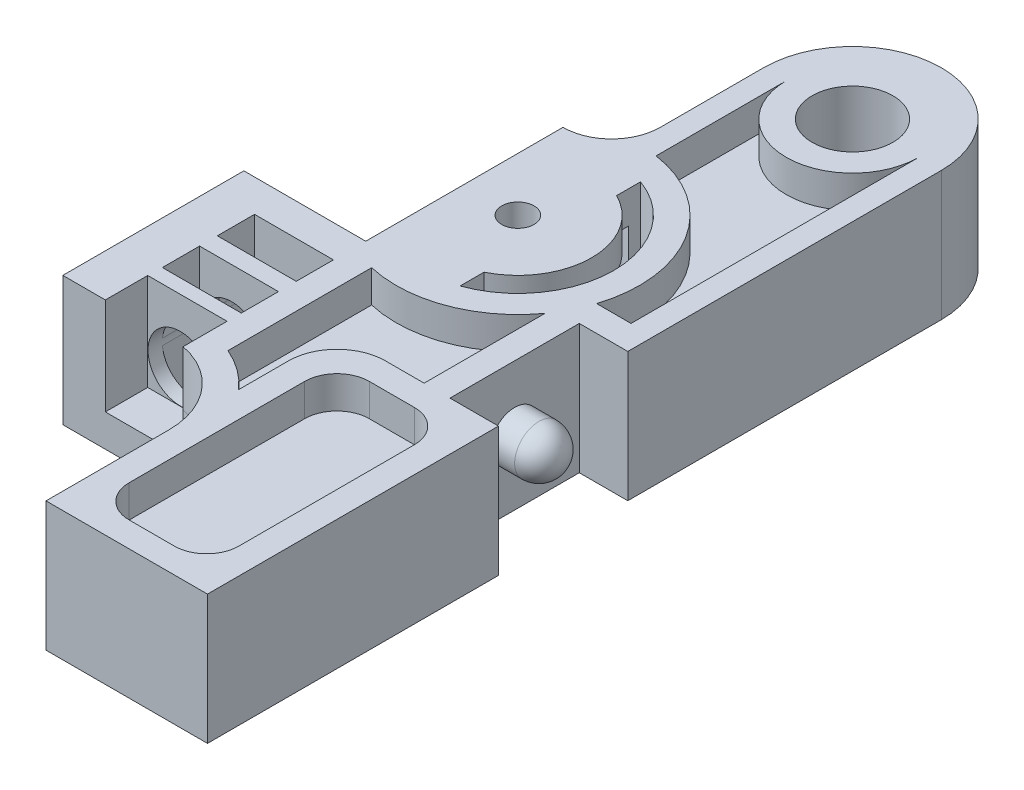
SolidWorks part; units mm, degrees
ref_plane "Front Plane" through (0, 0, 0) normal (0, 0, 1) x (1, 0, 0)
ref_plane "Top Plane" through (0, 0, 0) normal (0, 1, 0) x (1, 0, 0)
ref_plane "Right Plane" through (0, 0, 0) normal (1, 0, 0) x (0, 0, -1)
sketch "Sketch1" plane through (0, 0, 0) normal (0, 1, 0) x (1, 0, 0)
  line L1 (-21.56, 0) -> (-0.01, 0)
  line L2 (-21.56, 0) -> (-21.56, 50.9)
  line L3 (-21.56, 50.9) -> (-0.01, 50.9)
  line L4 (-0.01, 0) -> (-0.01, 50.9)
  dimension "D1" = 21.55
  dimension "D2" = 50.9
extrude "Boss-Extrude1" add sketch "Sketch1" along normal blind 8
sketch "Sketch2" plane through (0, 8, 0) normal (0, 1, 0) x (1, 0, 0)
  line L0 (-0.01, 0) -> (-0.01, 50.9) construction
  line L1 (-0.01, 50.9) -> (-21.56, 50.9) construction
  line L2 (-11.01, 45.4) -> (-11.01, 0) construction
  line L3 (-11.01, 39.0106) -> (-11.01, 45.4)
  line L4 (0, 0) -> (-0.01, 18)
  line L5 (-21.56, 0) -> (-0.01, 0) construction
  line L6 (4.9089, 18.5) -> (-33.8122, 18.5) construction
  line L7 (-37.2568, 26.1) -> (28.1891, 26.1) construction
  line L8 (-37.2568, 36) -> (-12.642, 36) construction
  line L9 (-14.0206, 36) -> (-14.0206, 23.8)
  line L10 (-14.0206, 23.8) -> (-21.56, 23.8)
  line L11 (-21.56, 50.9) -> (-21.56, 0) construction
  line L12 (-21.56, 23.8) -> (-21.56, 12.6)
  line L13 (-14.21, 36.006) -> (-14.21, 0) construction
  line L14 (-0.01, 45.4) -> (-0.01, 26)
  line L15 (-3.01, 26) -> (-3.01, 18)
  line L16 (-3.01, 22) -> (-7.4638, 22) construction
  line L17 (-0.01, 18) -> (-3.01, 18)
  line L18 (-0.01, 26) -> (-3.01, 26)
  line L19 (0, 0) -> (-10, 0)
  line L20 (-21.56, 12.6) -> (-10, 12.6)
  line L21 (-10, 12.6) -> (-10, 0)
  arc A0 (-0.01, 45.4) -> (-11.01, 45.4) centre (-5.51, 45.4) ccw
  arc A1 (-14.21, 36.006) -> (-11.01, 39.0106) centre (-14.0206, 39.0106) ccw
  dimension "D1" = 11
  dimension "D2" = 18
  dimension "D3" = 18.5
  dimension "D4" = 24.8
  dimension "D5" = 14.9
  dimension "D6" = 12.2
  dimension "D7" = 11.2
  dimension "D8" = 8
  dimension "D9" = 3
  dimension "D10" = 10
extrude "Cut-Extrude1" cut sketch "Sketch2" against normal blind 10
sketch "Sketch4" plane through (0, 8, 0) normal (0, 1, 0) x (1, 0, 0)
  line L0 (-17.8113, 29.9) -> (-3.6087, 29.9) construction
  line L1 (-0.01, 26) -> (-0.01, 45.4) construction
  circle A0 centre (-10.71, 29.9) radius 1
  dimension "D1" = 2
  dimension "D2" = 10.7
extrude "Cut-Extrude2" cut sketch "Sketch4" against normal blind 10
sketch "Sketch5" plane through (0, 8, 0) normal (0, 1, 0) x (1, 0, 0)
  circle A0 centre (-10.71, 29.9) radius 5.25
  dimension "D1" = 10.5
extrude "Cut-Extrude3" cut sketch "Sketch5" against normal blind 4 from offset 2 offset against normal yes
sketch "Sketch6" plane through (0, 8, 0) normal (0, 1, 0) x (1, 0, 0)
  line L0 (-8.7036, 35.4826) -> (-8.7036, 33.9999)
  line L1 (-8.7036, 25.8001) -> (-8.7036, 24.3174)
  arc A0 (-8.7036, 25.8001) -> (-8.7036, 33.9999) centre (-10.71, 29.9) ccw
  arc A1 (-8.7036, 24.3174) -> (-8.7036, 35.4826) centre (-10.71, 29.9) ccw
extrude "Cut-Extrude4" cut sketch "Sketch6" against normal blind 8
sketch "Sketch7" plane through (0, 8, 0) normal (0, 1, 0) x (1, 0, 0)
  circle A0 centre (-5.51, 45.4) radius 2.5
  dimension "D1" = 5
extrude "Cut-Extrude5" cut sketch "Sketch7" against normal blind 8
sketch "Sketch8" plane through (-3.01, 0, 0) normal (1, 0, 0) x (0, 0, -1)
  circle A0 centre (22, 4) radius 1.5
  dimension "D1" = 3
extrude "Boss-Extrude2" add sketch "Sketch8" along normal up to surface (3 mm away) up to face at (-0.01, 4, -35.7)
fillet "Fillet1" radius 1.5 1 edges at (-0.01, 4, -20.5)
sketch "Sketch9" plane through (0, 0, -12.6) normal (0, 0, 1) x (1, 0, 0)
  line L0 (-18.91, 4.0136) -> (-18.91, 7.1253) construction
  line L1 (-21.56, 0) -> (-21.56, 8) construction
  circle A0 centre (-16.91, 4.0136) radius 2
  dimension "D1" = 4
  dimension "D2" = 2.65
extrude "Cut-Extrude6" cut sketch "Sketch9" against normal up to next
fillet "Fillet2" radius 5 1 edges at (-10, 4, -12.6)
sketch "Sketch10" plane through (0, 8, 0) normal (0, 1, 0) x (1, 0, 0)
  line L0 (-21.56, 23.8) -> (-14.0206, 23.8) construction
  line L1 (-18.9, 21.8) -> (-14.0206, 21.8)
  line L2 (-18.9, 21.8) -> (-18.9, 19.5)
  line L3 (-18.9, 19.5) -> (-14.0206, 19.5)
  line L4 (-14.0206, 21.8) -> (-14.0206, 19.5)
  line L5 (-21.56, 23.8) -> (-21.56, 12.6) construction
  line L6 (-14.0206, 36) -> (-14.0206, 23.8) construction
  line L7 (-18.9, 18.4) -> (-14.0206, 18.4)
  line L8 (-18.9, 18.4) -> (-18.9, 16.1)
  line L9 (-18.9, 16.1) -> (-14.0206, 16.1)
  line L10 (-14.0206, 18.4) -> (-14.0206, 16.1)
  point P4 (-17.7903, 23.8)
  dimension "D1" = 2
  dimension "D2" = 2.66
  dimension "D3" = 2.3
  dimension "D4" = 2.3
  dimension "D5" = 1.1
extrude "Cut-Extrude7" cut sketch "Sketch10" against normal blind 8
sketch "Sketch11" plane through (0, 8, 0) normal (0, 1, 0) x (1, 0, 0)
  line L1 (-18.929, 15.2204) -> (-14.0206, 15.2204)
  line L2 (-18.929, 15.2204) -> (-18.929, 12.5031)
  line L3 (-18.929, 12.5031) -> (-14.0206, 12.5031)
  line L4 (-14.0206, 15.2204) -> (-14.0206, 12.5031)
  arc A0 (-10, 7.6) -> (-15, 12.6) centre (-15, 7.6) ccw construction
extrude "Cut-Extrude8" cut sketch "Sketch11" against normal blind 6
sketch "Sketch12" plane through (0, 8, 0) normal (0, 1, 0) x (1, 0, 0)
  line L0 (-9.61, 45.4) -> (-9.61, 37.3515)
  line L1 (-1.41, 45.4) -> (-1.41, 27.6)
  line L2 (-1.41, 27.6) -> (-3.5375, 27.6)
  line L3 (-0.01, 26) -> (-3.01, 26) construction
  arc A0 (-9.61, 45.4) -> (-1.41, 45.4) centre (-5.51, 45.4) ccw
  arc A1 (-3.5375, 27.6) -> (-9.61, 37.3515) centre (-10.71, 29.9) ccw
  arc A2 (-8.7036, 24.3174) -> (-8.7036, 35.4826) centre (-10.71, 29.9) ccw construction
  circle A3 centre (-5.51, 45.4) radius 2.5 construction
  dimension "D1" = 1.6
  dimension "D2" = 1.6
  dimension "D3" = 1.6
extrude "Cut-Extrude9" cut sketch "Sketch12" against normal blind 2
sketch "Sketch13" plane through (0, 0, 0) normal (0, -1, 0) x (1, 0, 0)
  line L0 (-3.5375, -27.6) -> (-1.41, -27.6)
  line L1 (-1.41, -27.6) -> (-1.41, -45.4)
  line L2 (-9.61, -37.3515) -> (-9.61, -45.4)
  circle A0 centre (-5.51, -45.4) radius 4.1
  arc A1 (-9.61, -37.3515) -> (-3.5375, -27.6) centre (-10.71, -29.9) ccw
extrude "Cut-Extrude11" cut sketch "Sketch13" against normal blind 2 contours A1 L2 A0 L1 L0
sketch "Sketch14" plane through (0, 8, 0) normal (0, 1, 0) x (1, 0, 0)
  line L0 (-12.4206, 22.5646) -> (-12.4206, 13.6751)
  line L1 (-4.61, 25.4813) -> (-4.61, 18)
  line L2 (-3.01, 26) -> (-3.01, 18) construction
  line L3 (-14.0206, 16.1) -> (-14.0206, 18.4) construction
  line L4 (-0.01, 0) -> (-0.01, 18) construction
  line L5 (-6.4, 16.4) -> (-3.61, 16.4)
  line L6 (-8.4, 14.4) -> (-8.4, 1.5468)
  line L7 (-8.4, 1.5468) -> (-1.61, 1.5468)
  line L8 (-1.61, 14.4) -> (-1.61, 1.5468)
  line L10 (-10, 7.6) -> (-10, 0) construction
  line L11 (-0.01, 18) -> (-3.01, 18) construction
  line L12 (-4.61, 18) -> (-10, 18)
  line L13 (-10, 18) -> (-10, 11.9081)
  arc A0 (-12.4206, 22.5646) -> (-4.61, 25.4813) centre (-10.71, 29.9) ccw
  arc A1 (-3.5375, 27.6) -> (-9.61, 37.3515) centre (-10.71, 29.9) ccw construction
  arc A2 (-10, 11.9081) -> (-12.4206, 13.6751) centre (-15, 7.6) ccw
  arc A3 (-10, 7.6) -> (-14.0206, 12.5031) centre (-15, 7.6) ccw construction
  arc A4 (-3.61, 16.4) -> (-1.61, 14.4) centre (-3.61, 14.4) cw
  arc A5 (-6.4, 16.4) -> (-8.4, 14.4) centre (-6.4, 14.4) ccw
  point P12 (-14.0206, 17.25)
  dimension "D3" = 1.6
  dimension "D7" = 2
  dimension "D1" = 1.6
  dimension "D2" = 1.6
  dimension "D4" = 1.6
  dimension "D5" = 1.6
  dimension "D6" = 1.6
  dimension "D8" = 1.6
  dimension "D9" = 1.6
extrude "Cut-Extrude12" cut sketch "Sketch14" against normal blind 2
fillet "Fillet3" radius 3 1 edges at (-10, 7, -18)
fillet "Fillet4" radius 2 2 edges at (-8.4, 7, -1.5468) (-1.61, 7, -1.5468)
sketch "Sketch15" plane through (0, 0, 0) normal (0, -1, 0) x (-1, 0, 0)
  line L0 (1.61, 3.5468) -> (1.61, 14.4) construction
  line L1 (6.4, 1.5468) -> (3.61, 1.5468)
  line L2 (8.4, 3.5468) -> (8.4, 14.4)
  line L3 (6.4, 16.4) -> (3.61, 16.4)
  line L4 (1.61, 3.5468) -> (1.61, 14.4)
  line L5 (6.4, 1.5468) -> (3.61, 1.5468) construction
  line L6 (4.61, 18) -> (4.61, 25.4813)
  line L7 (12.4206, 13.6751) -> (12.4206, 22.5646)
  line L8 (4.61, 18) -> (7, 18)
  line L9 (10, 11.9081) -> (10, 15)
  arc A1 (4.61, 25.4813) -> (12.4206, 22.5646) centre (10.71, 29.9) ccw
  arc A2 (12.4206, 13.6751) -> (10, 11.9081) centre (15, 7.6) ccw
  arc A3 (8.4, 14.4) -> (6.4, 16.4) centre (6.4, 14.4) ccw
  arc A4 (3.61, 16.4) -> (1.61, 14.4) centre (3.61, 14.4) ccw
  arc A5 (3.61, 1.5468) -> (1.61, 3.5468) centre (3.61, 3.5468) cw
  arc A6 (6.4, 1.5468) -> (8.4, 3.5468) centre (6.4, 3.5468) ccw
  arc A7 (7, 18) -> (10, 15) centre (7, 15) cw
  point P30 (1.61, 1.5468)
  dimension "D1" = 2
  dimension "D2" = 3
extrude "Cut-Extrude13" cut sketch "Sketch15" against normal blind 2 contours L4 L1 L2 L3 | A2 L7 A1 L6 L8 L9
sketch "Sketch16" plane through (-21.56, 0, 0) normal (-1, 0, 0) x (0, 0, 1)
  line L0 (-23.8, 0) -> (-23.8, 8) construction
  line L1 (-23.8, 5.5) -> (-21.8, 5.5)
  line L2 (-23.8, 5.5) -> (-23.8, 2.5)
  line L3 (-23.8, 2.5) -> (-21.8, 2.5)
  line L4 (-21.8, 5.5) -> (-21.8, 2.5)
  line L7 (-23.8, 0) -> (-12.6, 0) construction
  line L8 (-22.3678, 8) -> (-25.4813, 8) construction
  dimension "D1" = 2
  dimension "D2" = 3
  dimension "D3" = 2.5
extrude "Cut-Extrude14" cut sketch "Sketch16" against normal blind 7
sketch "Sketch17" plane through (0, 0, -23.8) normal (0, 0, -1) x (-1, 0, 0)
  line L0 (15.6028, 2.5) -> (18.2172, 2.5)
  line L1 (15.5718, 5.5) -> (18.2482, 5.5)
  arc A0 (15.6028, 2.5) -> (18.2172, 2.5) centre (16.91, 4.0136) ccw
  arc A1 (18.2482, 5.5) -> (15.5718, 5.5) centre (16.91, 4.0136) ccw
extrude "Boss-Extrude3" add sketch "Sketch17" against normal up to surface (2 mm away) up to face at (-16.7001, 4.0023, -21.8)
